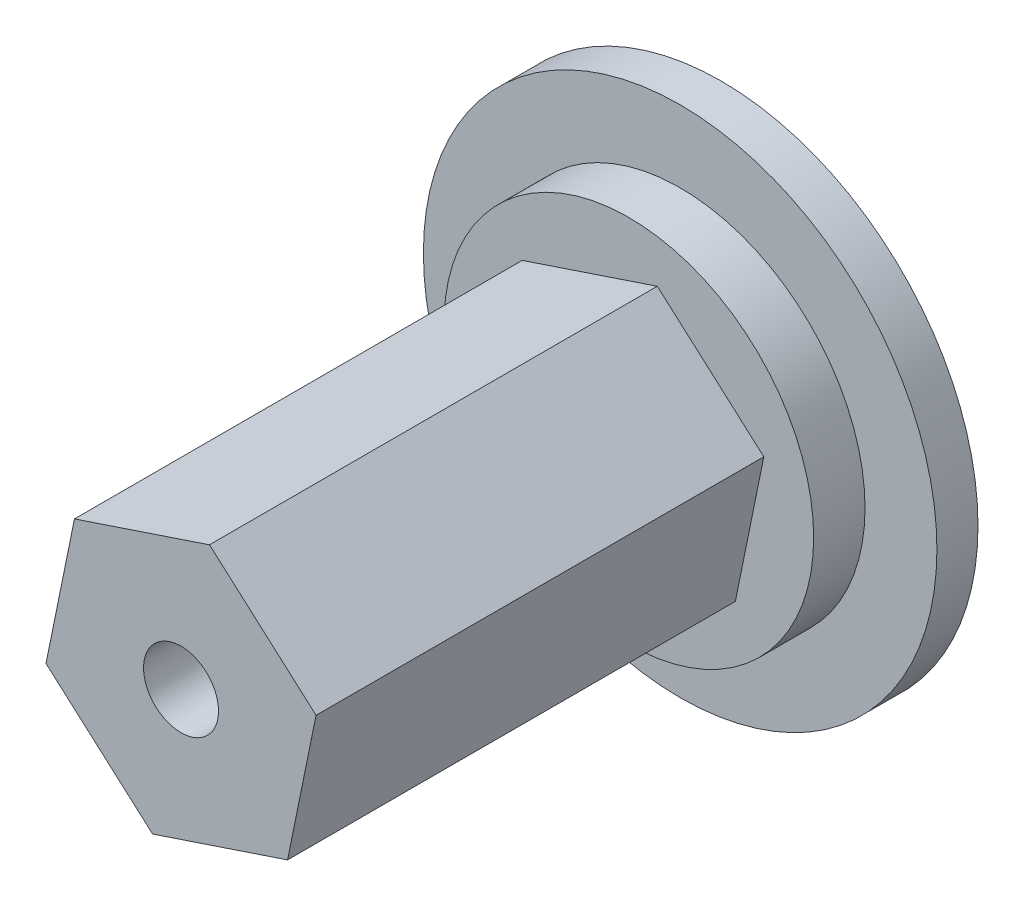
SolidWorks part; units mm, degrees
ref_plane "前视基准面" through (0, 0, 0) normal (0, 0, 1) x (1, 0, 0)
ref_plane "上视基准面" through (0, 0, 0) normal (0, 1, 0) x (1, 0, 0)
ref_plane "右视基准面" through (0, 0, 0) normal (1, 0, 0) x (0, 0, -1)
other "Configuration Table"
sketch "草图1" plane through (0, 0, 0) normal (0, 0, 1) x (1, 0, 0)
  circle A0 centre (0, 0) radius 12.5
  dimension "D1" = 25
extrude "凸台-拉伸1" add sketch "草图1" along normal blind 2
sketch "草图2" plane through (0, 0, 2) normal (0, 0, 1) x (1, 0, 0)
  circle A0 centre (0, 0) radius 9
  dimension "D1" = 18
extrude "凸台-拉伸2" add sketch "草图2" along normal blind 2.5
sketch "草图3" plane through (0, 0, 4.5) normal (0, 0, 1) x (1, 0, 0)
  line L1 (5.1874, -4.5952) -> (6.5732, 2.1949)
  line L2 (6.5732, 2.1949) -> (1.3858, 6.79)
  line L3 (1.3858, 6.79) -> (-5.1874, 4.5952)
  line L4 (-5.1874, 4.5952) -> (-6.5732, -2.1949)
  line L5 (-6.5732, -2.1949) -> (-1.3858, -6.79)
  line L6 (-1.3858, -6.79) -> (5.1874, -4.5952)
  circle A0 centre (0, 0) radius 6.0016 construction
  dimension "D1" = 13.86
extrude "凸台-拉伸3" add sketch "草图3" along normal blind 21.8
sketch "草图4" plane through (0, 0, 26.3) normal (0, 0, 1) x (1, 0, 0)
  circle A0 centre (0, 0) radius 1.825
  dimension "D1" = 3.65
extrude "切除-拉伸1" cut sketch "草图4" against normal through all
sketch "草图5" plane through (0, 0, 0) normal (0, 0, -1) x (-1, 0, 0)
  circle A0 centre (0, 0) radius 6.25
extrude "切除-拉伸2" cut sketch "草图5" against normal blind 2
